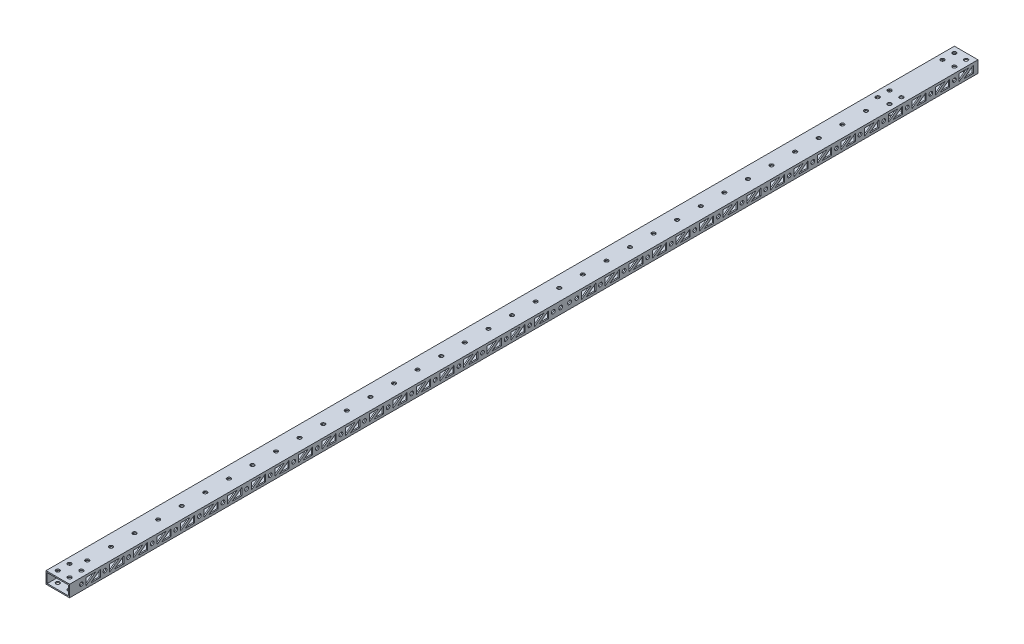
SolidWorks part; units mm, degrees
ref_plane "前视基准面" through (0, 0, 0) normal (0, 0, 1) x (1, 0, 0)
ref_plane "上视基准面" through (0, 0, 0) normal (0, 1, 0) x (1, 0, 0)
ref_plane "右视基准面" through (0, 0, 0) normal (1, 0, 0) x (0, 0, -1)
other "Configuration Table"
sketch "草图1" plane through (0, 0, 0) normal (0, 0, 1) x (1, 0, 0)
  line L1 (0, 0) -> (20, 0)
  line L2 (0, 0) -> (0, -10)
  line L3 (0, -10) -> (20, -10)
  line L4 (20, 0) -> (20, -10)
  dimension "D1" = 20
  dimension "D2" = 10
extrude "拉伸-薄壁1" add sketch "草图1" along normal blind 770 thin
sketch "草图2" plane through (0, -10, 0) normal (0, -1, 0) x (1, 0, 0)
  line L0 (20, 10) -> (0, 10) construction
  line L1 (20, 770) -> (20, 0) construction
  line L2 (0, 770) -> (0, 0) construction
  line L3 (10, 0) -> (10, 10) construction
  line L4 (0, 0) -> (20, 0) construction
  line L5 (10, 10) -> (10, 85) construction
  line L6 (0, 385) -> (20, 385) construction
  line L7 (10, 770) -> (10, 760) construction
  line L8 (20, 760) -> (0, 760) construction
  line L9 (0, 65) -> (20, 65) construction
  circle A0 centre (5, 5) radius 1.575
  circle A1 centre (15, 5) radius 1.575
  circle A2 centre (15, 15) radius 1.575
  circle A3 centre (5, 15) radius 1.575
  circle A4 centre (10, 85) radius 1.575
  circle A5 centre (10, 105) radius 1.575
  circle A6 centre (10, 125) radius 1.575
  circle A7 centre (10, 145) radius 1.575
  circle A8 centre (10, 165) radius 1.575
  circle A9 centre (10, 185) radius 1.575
  circle A10 centre (10, 205) radius 1.575
  circle A11 centre (10, 225) radius 1.575
  circle A12 centre (10, 245) radius 1.575
  circle A13 centre (10, 265) radius 1.575
  circle A14 centre (10, 285) radius 1.575
  circle A15 centre (10, 305) radius 1.575
  circle A16 centre (10, 325) radius 1.575
  circle A17 centre (10, 345) radius 1.575
  circle A18 centre (10, 365) radius 1.575
  circle A19 centre (10, 385) radius 1.575
  circle A20 centre (10, 405) radius 1.575
  circle A21 centre (10, 425) radius 1.575
  circle A22 centre (10, 445) radius 1.575
  circle A23 centre (10, 465) radius 1.575
  circle A24 centre (10, 485) radius 1.575
  circle A25 centre (10, 505) radius 1.575
  circle A26 centre (10, 525) radius 1.575
  circle A27 centre (10, 545) radius 1.575
  circle A28 centre (10, 565) radius 1.575
  circle A29 centre (10, 585) radius 1.575
  circle A30 centre (10, 605) radius 1.575
  circle A31 centre (10, 625) radius 1.575
  circle A32 centre (10, 645) radius 1.575
  circle A33 centre (10, 665) radius 1.575
  circle A34 centre (10, 685) radius 1.575
  circle A35 centre (10, 705) radius 1.575
  circle A36 centre (10, 725) radius 1.575
  circle A37 centre (5, 755) radius 1.575
  circle A38 centre (15, 755) radius 1.575
  circle A39 centre (15, 765) radius 1.575
  circle A40 centre (5, 765) radius 1.575
  circle A41 centre (10, 745) radius 1.575
  circle A42 centre (5, 70) radius 1.6
  circle A43 centre (15, 70) radius 1.6
  circle A44 centre (15, 60) radius 1.6
  circle A45 centre (5, 60) radius 1.6
  dimension "D1" = 3.15
  dimension "D5" = 3.15
  dimension "D10" = 3.2
  dimension "D2" = 5
  dimension "D3" = 5
  dimension "D4" = 10
  dimension "D6" = 75
  dimension "D8" = 20
  dimension "D9" = 55
  dimension "D11" = 5
  dimension "D12" = 5
  dimension "D7" = 34
extrude "切除-拉伸1" cut sketch "草图2" against normal through all
sketch "草图4" plane through (20, 0, 0) normal (1, 0, 0) x (0, 0, -1)
  line L0 (0, -5) -> (-770, -5) construction
  line L1 (0, -10) -> (0, 0) construction
  line L2 (-770, -10) -> (-770, 0) construction
  line L3 (-4, -2) -> (-4, -8)
  line L4 (-4, -8) -> (-12, -8)
  line L5 (-12, -8) -> (-4, -2)
  line L6 (-8, -2) -> (-16, -8)
  line L7 (-16, -8) -> (-16, -2)
  line L8 (-16, -2) -> (-8, -2)
  line L9 (-770, -10) -> (0, -10) construction
  line L10 (-770, 0) -> (0, 0) construction
  line L11 (-24, -2) -> (-24, -8)
  line L12 (-24, -8) -> (-32, -8)
  line L13 (-32, -8) -> (-24, -2)
  line L14 (-36, -2) -> (-28, -2)
  line L15 (-28, -2) -> (-36, -8)
  line L16 (-36, -8) -> (-36, -2)
  line L17 (-44, -2) -> (-44, -8)
  line L18 (-44, -8) -> (-52, -8)
  line L19 (-52, -8) -> (-44, -2)
  line L20 (-56, -2) -> (-48, -2)
  line L21 (-48, -2) -> (-56, -8)
  line L22 (-56, -8) -> (-56, -2)
  line L23 (-64, -2) -> (-64, -8)
  line L24 (-64, -8) -> (-72, -8)
  line L25 (-72, -8) -> (-64, -2)
  line L26 (-76, -2) -> (-68, -2)
  line L27 (-68, -2) -> (-76, -8)
  line L28 (-76, -8) -> (-76, -2)
  line L29 (-84, -2) -> (-84, -8)
  line L30 (-84, -8) -> (-92, -8)
  line L31 (-92, -8) -> (-84, -2)
  line L32 (-96, -2) -> (-88, -2)
  line L33 (-88, -2) -> (-96, -8)
  line L34 (-96, -8) -> (-96, -2)
  line L35 (-104, -2) -> (-104, -8)
  line L36 (-104, -8) -> (-112, -8)
  line L37 (-112, -8) -> (-104, -2)
  line L38 (-116, -2) -> (-108, -2)
  line L39 (-108, -2) -> (-116, -8)
  line L40 (-116, -8) -> (-116, -2)
  line L41 (-124, -2) -> (-124, -8)
  line L42 (-124, -8) -> (-132, -8)
  line L43 (-132, -8) -> (-124, -2)
  line L44 (-136, -2) -> (-128, -2)
  line L45 (-128, -2) -> (-136, -8)
  line L46 (-136, -8) -> (-136, -2)
  line L47 (-144, -2) -> (-144, -8)
  line L48 (-144, -8) -> (-152, -8)
  line L49 (-152, -8) -> (-144, -2)
  line L50 (-156, -2) -> (-148, -2)
  line L51 (-148, -2) -> (-156, -8)
  line L52 (-156, -8) -> (-156, -2)
  line L53 (-164, -2) -> (-164, -8)
  line L54 (-164, -8) -> (-172, -8)
  line L55 (-172, -8) -> (-164, -2)
  line L56 (-176, -2) -> (-168, -2)
  line L57 (-168, -2) -> (-176, -8)
  line L58 (-176, -8) -> (-176, -2)
  line L59 (-184, -2) -> (-184, -8)
  line L60 (-184, -8) -> (-192, -8)
  line L61 (-192, -8) -> (-184, -2)
  line L62 (-196, -2) -> (-188, -2)
  line L63 (-188, -2) -> (-196, -8)
  line L64 (-196, -8) -> (-196, -2)
  line L65 (-204, -2) -> (-204, -8)
  line L66 (-204, -8) -> (-212, -8)
  line L67 (-212, -8) -> (-204, -2)
  line L68 (-216, -2) -> (-208, -2)
  line L69 (-208, -2) -> (-216, -8)
  line L70 (-216, -8) -> (-216, -2)
  line L71 (-224, -2) -> (-224, -8)
  line L72 (-224, -8) -> (-232, -8)
  line L73 (-232, -8) -> (-224, -2)
  line L74 (-236, -2) -> (-228, -2)
  line L75 (-228, -2) -> (-236, -8)
  line L76 (-236, -8) -> (-236, -2)
  line L77 (-244, -2) -> (-244, -8)
  line L78 (-244, -8) -> (-252, -8)
  line L79 (-252, -8) -> (-244, -2)
  line L80 (-256, -2) -> (-248, -2)
  line L81 (-248, -2) -> (-256, -8)
  line L82 (-256, -8) -> (-256, -2)
  line L83 (-264, -2) -> (-264, -8)
  line L84 (-264, -8) -> (-272, -8)
  line L85 (-272, -8) -> (-264, -2)
  line L86 (-276, -2) -> (-268, -2)
  line L87 (-268, -2) -> (-276, -8)
  line L88 (-276, -8) -> (-276, -2)
  line L89 (-284, -2) -> (-284, -8)
  line L90 (-284, -8) -> (-292, -8)
  line L91 (-292, -8) -> (-284, -2)
  line L92 (-296, -2) -> (-288, -2)
  line L93 (-288, -2) -> (-296, -8)
  line L94 (-296, -8) -> (-296, -2)
  line L95 (-304, -2) -> (-304, -8)
  line L96 (-304, -8) -> (-312, -8)
  line L97 (-312, -8) -> (-304, -2)
  line L98 (-316, -2) -> (-308, -2)
  line L99 (-308, -2) -> (-316, -8)
  line L100 (-316, -8) -> (-316, -2)
  line L101 (-324, -2) -> (-324, -8)
  line L102 (-324, -8) -> (-332, -8)
  line L103 (-332, -8) -> (-324, -2)
  line L104 (-336, -2) -> (-328, -2)
  line L105 (-328, -2) -> (-336, -8)
  line L106 (-336, -8) -> (-336, -2)
  line L113 (-364, -2) -> (-364, -8)
  line L114 (-364, -8) -> (-372, -8)
  line L115 (-372, -8) -> (-364, -2)
  line L116 (-376, -2) -> (-368, -2)
  line L117 (-368, -2) -> (-376, -8)
  line L118 (-376, -8) -> (-376, -2)
  line L119 (-384, -2) -> (-384, -8)
  line L120 (-384, -8) -> (-392, -8)
  line L121 (-392, -8) -> (-384, -2)
  line L122 (-396, -2) -> (-388, -2)
  line L123 (-388, -2) -> (-396, -8)
  line L124 (-396, -8) -> (-396, -2)
  line L125 (-404, -2) -> (-404, -8)
  line L126 (-404, -8) -> (-412, -8)
  line L127 (-412, -8) -> (-404, -2)
  line L128 (-416, -2) -> (-408, -2)
  line L129 (-408, -2) -> (-416, -8)
  line L130 (-416, -8) -> (-416, -2)
  line L131 (-424, -2) -> (-424, -8)
  line L132 (-424, -8) -> (-432, -8)
  line L133 (-432, -8) -> (-424, -2)
  line L134 (-436, -2) -> (-428, -2)
  line L135 (-428, -2) -> (-436, -8)
  line L136 (-436, -8) -> (-436, -2)
  line L137 (-444, -2) -> (-444, -8)
  line L138 (-444, -8) -> (-452, -8)
  line L139 (-452, -8) -> (-444, -2)
  line L140 (-456, -2) -> (-448, -2)
  line L141 (-448, -2) -> (-456, -8)
  line L142 (-456, -8) -> (-456, -2)
  line L143 (-464, -2) -> (-464, -8)
  line L144 (-464, -8) -> (-472, -8)
  line L145 (-472, -8) -> (-464, -2)
  line L146 (-476, -2) -> (-468, -2)
  line L147 (-468, -2) -> (-476, -8)
  line L148 (-476, -8) -> (-476, -2)
  line L149 (-484, -2) -> (-484, -8)
  line L150 (-484, -8) -> (-492, -8)
  line L151 (-492, -8) -> (-484, -2)
  line L152 (-496, -2) -> (-488, -2)
  line L153 (-488, -2) -> (-496, -8)
  line L154 (-496, -8) -> (-496, -2)
  line L155 (-504, -2) -> (-504, -8)
  line L156 (-504, -8) -> (-512, -8)
  line L157 (-512, -8) -> (-504, -2)
  line L158 (-516, -2) -> (-508, -2)
  line L159 (-508, -2) -> (-516, -8)
  line L160 (-516, -8) -> (-516, -2)
  line L161 (-524, -2) -> (-524, -8)
  line L162 (-524, -8) -> (-532, -8)
  line L163 (-532, -8) -> (-524, -2)
  line L164 (-536, -2) -> (-528, -2)
  line L165 (-528, -2) -> (-536, -8)
  line L166 (-536, -8) -> (-536, -2)
  line L167 (-544, -2) -> (-544, -8)
  line L168 (-544, -8) -> (-552, -8)
  line L169 (-552, -8) -> (-544, -2)
  line L170 (-556, -2) -> (-548, -2)
  line L171 (-548, -2) -> (-556, -8)
  line L172 (-556, -8) -> (-556, -2)
  line L173 (-564, -2) -> (-564, -8)
  line L174 (-564, -8) -> (-572, -8)
  line L175 (-572, -8) -> (-564, -2)
  line L176 (-576, -2) -> (-568, -2)
  line L177 (-568, -2) -> (-576, -8)
  line L178 (-576, -8) -> (-576, -2)
  line L179 (-584, -2) -> (-584, -8)
  line L180 (-584, -8) -> (-592, -8)
  line L181 (-592, -8) -> (-584, -2)
  line L182 (-596, -2) -> (-588, -2)
  line L183 (-588, -2) -> (-596, -8)
  line L184 (-596, -8) -> (-596, -2)
  line L185 (-604, -2) -> (-604, -8)
  line L186 (-604, -8) -> (-612, -8)
  line L187 (-612, -8) -> (-604, -2)
  line L188 (-616, -2) -> (-608, -2)
  line L189 (-608, -2) -> (-616, -8)
  line L190 (-616, -8) -> (-616, -2)
  line L191 (-624, -2) -> (-624, -8)
  line L192 (-624, -8) -> (-632, -8)
  line L193 (-632, -8) -> (-624, -2)
  line L194 (-636, -2) -> (-628, -2)
  line L195 (-628, -2) -> (-636, -8)
  line L196 (-636, -8) -> (-636, -2)
  line L197 (-644, -2) -> (-644, -8)
  line L198 (-644, -8) -> (-652, -8)
  line L199 (-652, -8) -> (-644, -2)
  line L200 (-656, -2) -> (-648, -2)
  line L201 (-648, -2) -> (-656, -8)
  line L202 (-656, -8) -> (-656, -2)
  line L203 (-664, -2) -> (-664, -8)
  line L204 (-664, -8) -> (-672, -8)
  line L205 (-672, -8) -> (-664, -2)
  line L206 (-676, -2) -> (-668, -2)
  line L207 (-668, -2) -> (-676, -8)
  line L208 (-676, -8) -> (-676, -2)
  line L209 (-684, -2) -> (-684, -8)
  line L210 (-684, -8) -> (-692, -8)
  line L211 (-692, -8) -> (-684, -2)
  line L212 (-696, -2) -> (-688, -2)
  line L213 (-688, -2) -> (-696, -8)
  line L214 (-696, -8) -> (-696, -2)
  line L215 (-704, -2) -> (-704, -8)
  line L216 (-704, -8) -> (-712, -8)
  line L217 (-712, -8) -> (-704, -2)
  line L218 (-716, -2) -> (-708, -2)
  line L219 (-708, -2) -> (-716, -8)
  line L220 (-716, -8) -> (-716, -2)
  line L221 (-724, -2) -> (-724, -8)
  line L222 (-724, -8) -> (-732, -8)
  line L223 (-732, -8) -> (-724, -2)
  line L224 (-736, -2) -> (-728, -2)
  line L225 (-728, -2) -> (-736, -8)
  line L226 (-736, -8) -> (-736, -2)
  line L227 (-744, -2) -> (-744, -8)
  line L228 (-744, -8) -> (-752, -8)
  line L229 (-752, -8) -> (-744, -2)
  line L230 (-756, -2) -> (-748, -2)
  line L231 (-748, -2) -> (-756, -8)
  line L232 (-756, -8) -> (-756, -2)
  line L251 (-764, -2) -> (-764, -8) [skipped]
  line L252 (-764, -8) -> (-772, -8) [skipped]
  line L253 (-772, -8) -> (-764, -2) [skipped]
  line L254 (-776, -2) -> (-768, -2) [skipped]
  line L255 (-768, -2) -> (-776, -8) [skipped]
  line L256 (-776, -8) -> (-776, -2) [skipped]
  line L257 (-784, -2) -> (-784, -8) [skipped]
  line L258 (-784, -8) -> (-792, -8) [skipped]
  line L259 (-792, -8) -> (-784, -2) [skipped]
  line L260 (-796, -2) -> (-788, -2) [skipped]
  line L261 (-788, -2) -> (-796, -8) [skipped]
  line L262 (-796, -8) -> (-796, -2) [skipped]
  line L263 (-804, -2) -> (-804, -8) [skipped]
  line L264 (-804, -8) -> (-812, -8) [skipped]
  line L265 (-812, -8) -> (-804, -2) [skipped]
  line L266 (-816, -2) -> (-808, -2) [skipped]
  line L267 (-808, -2) -> (-816, -8) [skipped]
  line L268 (-816, -8) -> (-816, -2) [skipped]
  line L269 (-350, 0) -> (-350, -10) construction
  line L270 (-344, -2) -> (-344, -8) [skipped]
  line L271 (-344, -8) -> (-352, -8) [skipped]
  line L272 (-352, -8) -> (-344, -2) [skipped]
  line L273 (-356, -2) -> (-348, -2) [skipped]
  line L274 (-348, -2) -> (-356, -8) [skipped]
  line L275 (-356, -8) -> (-356, -2) [skipped]
  circle A0 centre (-20, -5) radius 1.575
  circle A1 centre (-40, -5) radius 1.575
  circle A2 centre (-60, -5) radius 1.575
  circle A3 centre (-80, -5) radius 1.575
  circle A4 centre (-100, -5) radius 1.575
  circle A5 centre (-120, -5) radius 1.575
  circle A6 centre (-140, -5) radius 1.575
  circle A7 centre (-160, -5) radius 1.575
  circle A8 centre (-180, -5) radius 1.575
  circle A9 centre (-200, -5) radius 1.575
  circle A10 centre (-220, -5) radius 1.575
  circle A11 centre (-240, -5) radius 1.575
  circle A12 centre (-260, -5) radius 1.575
  circle A13 centre (-280, -5) radius 1.575
  circle A14 centre (-300, -5) radius 1.575
  circle A15 centre (-320, -5) radius 1.575
  circle A16 centre (-340, -5) radius 1.575
  circle A17 centre (-360, -5) radius 1.575
  circle A18 centre (-380, -5) radius 1.575
  circle A19 centre (-400, -5) radius 1.575
  circle A20 centre (-420, -5) radius 1.575
  circle A21 centre (-440, -5) radius 1.575
  circle A22 centre (-460, -5) radius 1.575
  circle A23 centre (-480, -5) radius 1.575
  circle A24 centre (-500, -5) radius 1.575
  circle A25 centre (-520, -5) radius 1.575
  circle A26 centre (-540, -5) radius 1.575
  circle A27 centre (-560, -5) radius 1.575
  circle A28 centre (-580, -5) radius 1.575
  circle A29 centre (-600, -5) radius 1.575
  circle A30 centre (-620, -5) radius 1.575
  circle A31 centre (-640, -5) radius 1.575
  circle A32 centre (-660, -5) radius 1.575
  circle A33 centre (-680, -5) radius 1.575
  circle A34 centre (-700, -5) radius 1.575
  circle A35 centre (-720, -5) radius 1.575
  circle A36 centre (-740, -5) radius 1.575
  circle A37 centre (-760, -5) radius 1.575
  circle A41 centre (-780, -5) radius 1.575 [skipped]
  circle A42 centre (-800, -5) radius 1.575 [skipped]
  circle A43 centre (-820, -5) radius 1.575 [skipped]
  circle A44 centre (-353.75, -5) radius 1.6
  circle A45 centre (-346.25, -5) radius 1.6
  dimension "D2" = 3.15
  dimension "D15" = 3.2
  dimension "D1" = 20
  dimension "D3" = 20
  dimension "D4" = 8
  dimension "D5" = 6
  dimension "D6" = 6
  dimension "D7" = 2
  dimension "D8" = 2
  dimension "D9" = 12
  dimension "D10" = 4
  dimension "D12" = 20
  dimension "D14" = 350
  dimension "D16" = 3.75
  dimension "D13" = 41
  dimension "D11" = 41
extrude "切除-拉伸2" cut sketch "草图4" against normal through all
